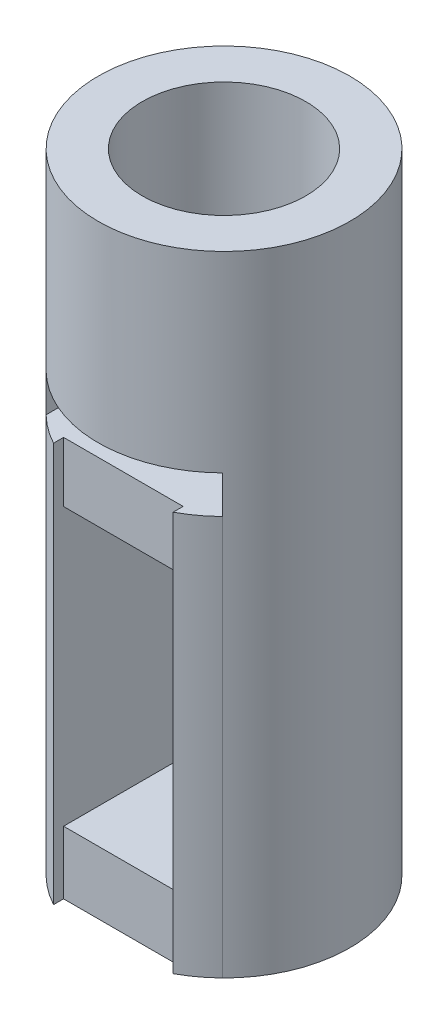
SolidWorks part; units mm, degrees
ref_plane "前视基准面" through (0, 0, 0) normal (0, 0, 1) x (1, 0, 0)
ref_plane "上视基准面" through (0, 0, 0) normal (0, 1, 0) x (1, 0, 0)
ref_plane "右视基准面" through (0, 0, 0) normal (1, 0, 0) x (0, 0, -1)
sketch "草图1" plane through (0, 0, 0) normal (0, 1, 0) x (1, 0, 0)
  circle A0 centre (0, 0) radius 10
  dimension "D1" = 20
extrude "凸台-拉伸1" add sketch "草图1" along normal blind 50
ref_plane "基准面1" through (0, 0, 10) normal (0, 0, 1) x (1, 0, 0)
sketch "草图2" plane through (0, 0, 10) normal (0, 0, 1) x (1, 0, 0)
  line L0 (-10, 0) -> (10, 0) construction
  line L1 (4.75, 0) -> (-4.75, 0)
  line L2 (4.75, 0) -> (4.75, 32)
  line L3 (4.75, 32) -> (-4.75, 32)
  line L4 (-4.75, 0) -> (-4.75, 32)
  line L5 (-4.75, 8.7599) -> (0, 8.7599) construction
  line L6 (0, 8.7599) -> (4.75, 8.7599) construction
  line L7 (0, 0) -> (0, 8.7599) construction
  dimension "D1" = 9.5
  dimension "D2" = 32
extrude "切除-拉伸1" cut sketch "草图2" against normal blind 2
sketch "草图3" plane through (0, 0, 8) normal (0, 0, 1) x (1, 0, 0)
  line L0 (0, 27) -> (0, 32) construction
  line L1 (-4.75, 27) -> (4.75, 27)
  line L2 (-4.75, 27) -> (-4.75, 5)
  line L3 (-4.75, 5) -> (4.75, 5)
  line L4 (4.75, 27) -> (4.75, 5)
  line L5 (-4.75, 32) -> (4.75, 32) construction
  line L6 (0, 5) -> (0, 0) construction
  dimension "D1" = 9.5
  dimension "D2" = 22
extrude "切除-拉伸2" cut sketch "草图3" against normal blind 14
sketch "草图4" plane through (0, 50, 0) normal (0, 1, 0) x (1, 0, 0)
  circle A0 centre (0, 0) radius 6.5
  dimension "D1" = 13
extrude "切除-拉伸3" cut sketch "草图4" against normal blind 18
sketch "草图5" plane through (0, 0, 10) normal (0, 0, 1) x (1, 0, 0)
  line L0 (0, 0) -> (0, 31.76) construction
  line L1 (-7, 31.76) -> (7, 31.76)
  line L2 (-7, 31.76) -> (-7, 34.76)
  line L3 (-7, 34.76) -> (7, 34.76)
  line L4 (7, 31.76) -> (7, 34.76)
  line L5 (-7, 33.26) -> (0, 33.26) construction
  line L6 (0, 33.26) -> (7, 33.26) construction
  dimension "D1" = 3
  dimension "D2" = 14
extrude "切除-拉伸4" cut sketch "草图5" against normal blind 10
